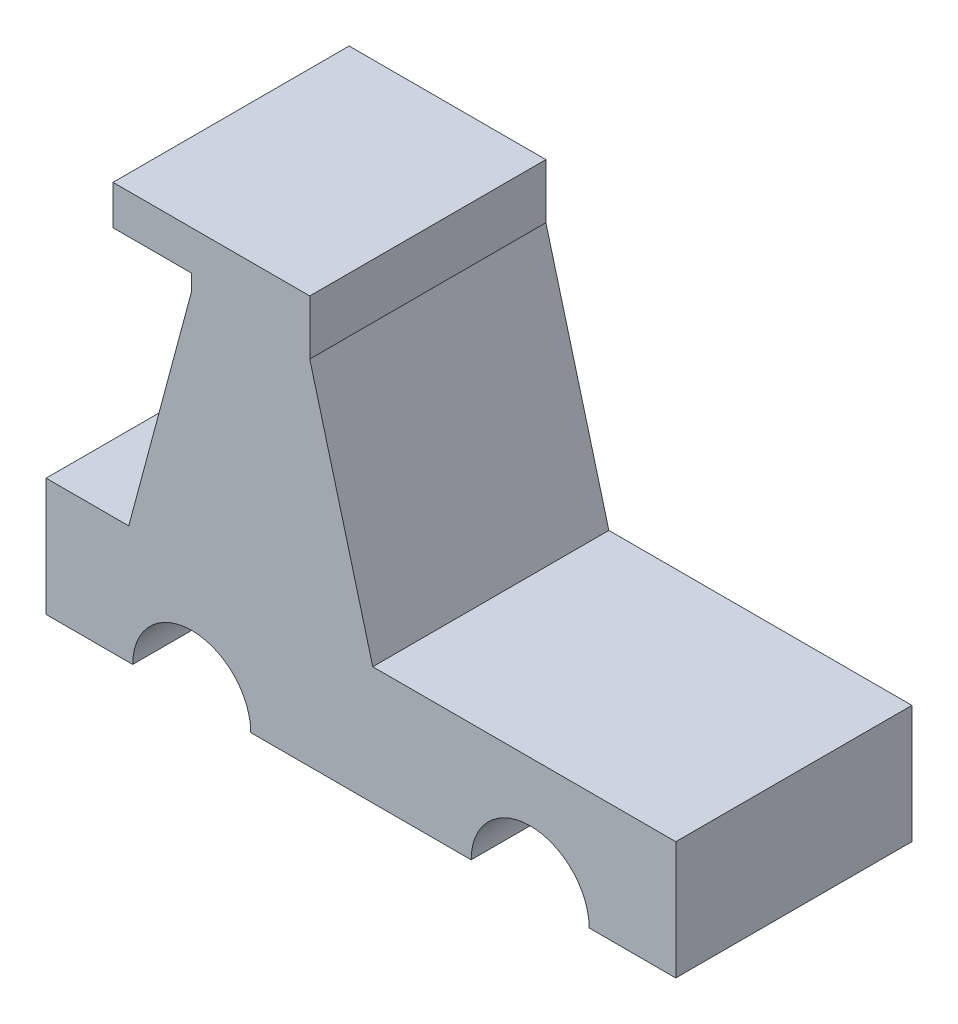
SolidWorks part; units mm, degrees
ref_plane "Front Plane" through (0, 0, 0) normal (0, 0, 1) x (1, 0, 0)
ref_plane "Top Plane" through (0, 0, 0) normal (0, 1, 0) x (1, 0, 0)
ref_plane "Right Plane" through (0, 0, 0) normal (1, 0, 0) x (0, 0, -1)
sketch "Sketch1" plane through (0, 0, 0) normal (0, 1, 0) x (1, 0, 0)
  line L1 (0, 0) -> (80, 0)
  line L2 (0, 0) -> (0, 30)
  line L3 (0, 30) -> (80, 30)
  line L4 (80, 0) -> (80, 30)
  dimension "D1" = 80
  dimension "D2" = 30
extrude "Boss-Extrude1" add sketch "Sketch1" along normal blind 30
sketch "Sketch2" plane through (0, 0, 0) normal (0, 0, 1) x (1, 0, 0)
  line L0 (40, 30) -> (40, 0) construction
  line L3 (0, 30) -> (80, 30) construction
  line L4 (0, 0) -> (80, 0) construction
  line L5 (80, 15) -> (0, 15) construction
  line L6 (80, 30) -> (80, 0) construction
  line L7 (0, 30) -> (0, 0) construction
  circle A1 centre (61.5, 15) radius 7.5
  circle A2 centre (18.5, 15) radius 7.5
  dimension "D1" = 15
  dimension "D2" = 21.5
extrude "Cut-Extrude1" cut sketch "Sketch2" against normal through all both and the other way through all
sketch "Sketch3" plane through (0, 0, 0) normal (0, 0, 1) x (1, 0, 0)
  line L0 (8.5, 61.8) -> (18.5, 61.8)
  line L1 (8.5, 61.8) -> (8.5, 66.8)
  line L2 (8.5, 66.8) -> (33.5, 66.8)
  line L3 (33.5, 66.8) -> (33.5, 59.8564)
  line L4 (0, 30) -> (80, 30) construction
  line L6 (18.5, 30) -> (18.5, 61.8)
  line L7 (10.5, 30) -> (18.5, 59.8564)
  line L8 (10.5, 30) -> (41.5, 30)
  line L9 (33.5, 59.8564) -> (41.5, 30)
  circle A0 centre (18.5, 15) radius 7.5 construction
  dimension "D1" = 46.8
  dimension "D2" = 10
  dimension "D3" = 10
  dimension "D4" = 6.9436
  dimension "D5" = 29.8564
  dimension "D6" = 75
  dimension "D7" = 5
  dimension "D8" = 75
  dimension "D9" = 29.8564
  dimension "D10" = 31
extrude "Boss-Extrude2" add sketch "Sketch3" against normal up to surface (30 mm away) contours L7 L8 L6 | L9 L3 L2 L1 L0 L6 L8 up to face at (69, 15, -30)
sketch "Sketch4" plane through (0, 0, 0) normal (0, 0, 1) x (1, 0, 0)
  line L0 (0, 0) -> (80, 0) construction
  line L1 (-10.0992, 15) -> (92.4574, 15)
  line L2 (-10.0992, 15) -> (-10.0992, -4.2435)
  line L3 (-10.0992, -4.2435) -> (92.4574, -4.2435)
  line L4 (92.4574, 15) -> (92.4574, -4.2435)
  dimension "D1" = 15
extrude "Cut-Extrude2" cut sketch "Sketch4" against normal through all both and the other way through all
